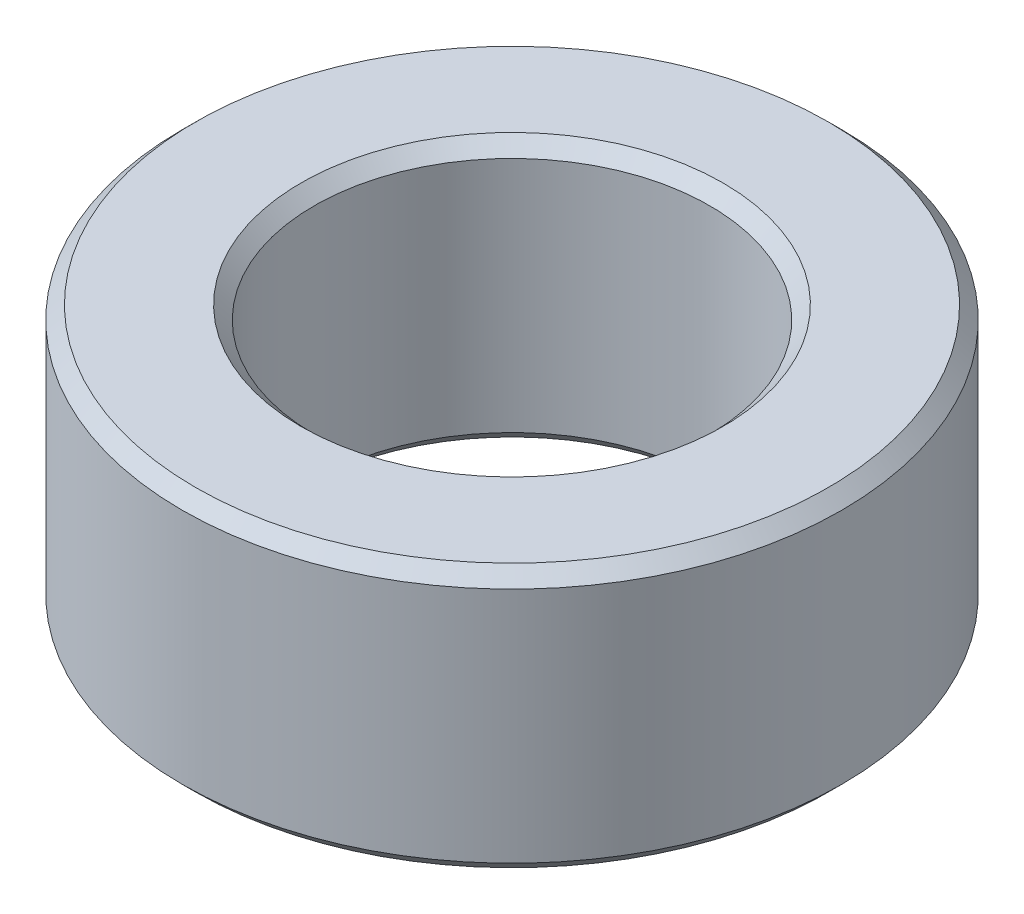
SolidWorks part; units mm, degrees
material "ABS PC"
ref_plane "前视基准面" through (0, 0, 0) normal (0, 0, 1) x (1, 0, 0)
ref_plane "上视基准面" through (0, 0, 0) normal (0, 1, 0) x (1, 0, 0)
ref_plane "右视基准面" through (0, 0, 0) normal (1, 0, 0) x (0, 0, -1)
sketch "草图1" plane through (0, 0, 0) normal (0, 1, 0) x (1, 0, 0)
  circle A0 centre (0, 0) radius 3
  circle A1 centre (0, 0) radius 5
  dimension "D1" = 6
  dimension "D2" = 10
extrude "凸台-拉伸1" add sketch "草图1" along normal blind 4 contours A1 A0
chamfer "倒角1" distance 0.2 angle 45 4 edges at (0, 0, 5) (0, 4, 5) (0, 0, 3) (0, 4, 3)
